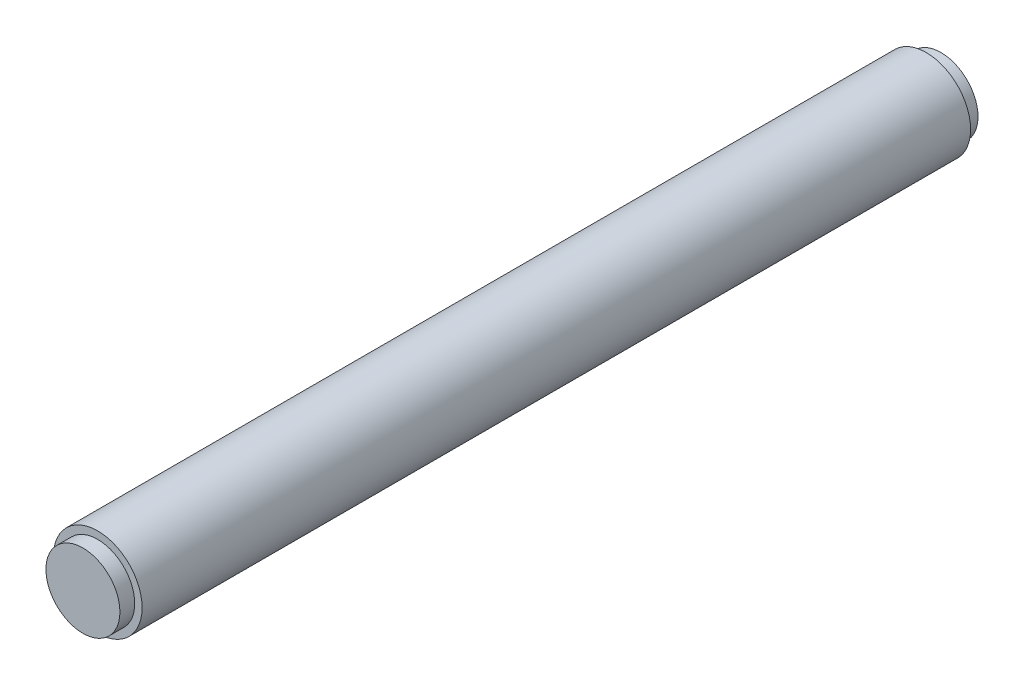
SolidWorks part; units mm, degrees
ref_plane "Alzado" through (0, 0, 0) normal (0, 0, 1) x (1, 0, 0)
ref_plane "Planta" through (0, 0, 0) normal (0, 1, 0) x (1, 0, 0)
ref_plane "Vista lateral" through (0, 0, 0) normal (1, 0, 0) x (0, 0, -1)
sketch "Croquis1" plane through (0, 0, 0) normal (0, 0, 1) x (1, 0, 0)
  circle A0 centre (-8.7373, 10.7454) radius 30
extrude "Saliente-Extruir1" add sketch "Croquis1" along normal blind 560
sketch "Croquis2" plane through (0, 0, 560) normal (0, 0, 1) x (1, 0, 0)
  circle A0 centre (-8.7373, 10.7454) radius 25
extrude "Saliente-Extruir2" add sketch "Croquis2" along normal blind 10
sketch "Croquis3" plane through (0, 0, 0) normal (0, 0, -1) x (-1, 0, 0)
  circle A0 centre (8.7373, 10.7454) radius 25
extrude "Saliente-Extruir3" add sketch "Croquis3" along normal blind 10
